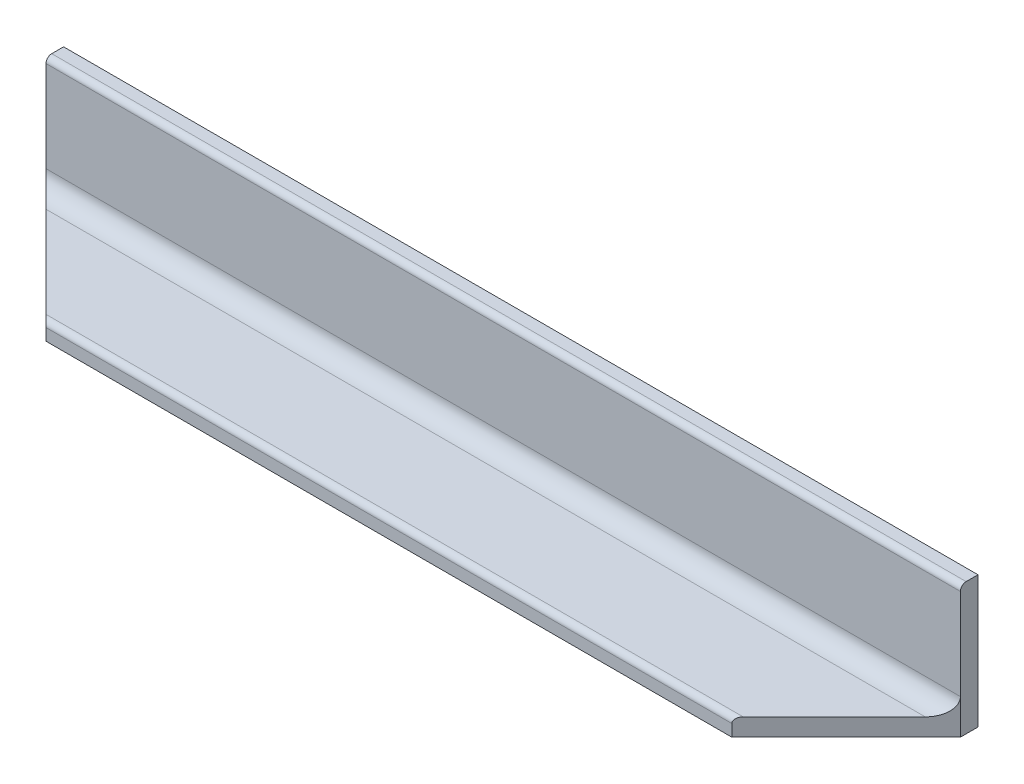
SolidWorks part; units mm, degrees
material "СТ3КП"
ref_plane "Спереди" through (0, 0, 0) normal (0, 0, 1) x (1, 0, 0)
ref_plane "Сверху" through (0, 0, 0) normal (0, 1, 0) x (1, 0, 0)
ref_plane "Справа" through (0, 0, 0) normal (1, 0, 0) x (0, 0, -1)
sketch "Эскиз1" plane through (0, 0, 0) normal (1, 0, 0) x (0, 0, -1)
  line L0 (0, -39.9784) -> (0, 49.0833) construction
  line B0 (0, 0) -> (0, 30)
  line B1 (0, 30) -> (-2.7, 30)
  line B2 (-4, 28.7) -> (-4, 8)
  line B3 (-8, 4) -> (-28.7, 4)
  line B4 (-30, 2.7) -> (-30, 0)
  line B5 (-30, 0) -> (0, 0)
  arc B6 (-2.7, 30) -> (-4, 28.7) centre (-2.7, 28.7) ccw
  arc B7 (-28.7, 4) -> (-30, 2.7) centre (-28.7, 2.7) ccw
  arc B8 (-4, 8) -> (-8, 4) centre (-8, 8) cw
sketch_block_instance "Уголок 30х30х4-1"
sketch_block "Уголок 30х30х4" parameters "D4"=1.3, "D6"=4, "D1"=30, "D2"=30, "D3"=45, "D5"=4
extrude "Бобышка-Вытянуть1" add sketch "Эскиз1" along normal mid plane 208
sketch "Эскиз2" plane through (0, 0, 0) normal (0, -1, 0) x (1, 0, 0)
  line L0 (-104, 4) -> (-78, 30)
  line L1 (104, 30) -> (-104, 30) construction
  line L2 (-78, 30) -> (-104, 30)
  line L3 (-104, 30) -> (-104, 4)
  line L4 (104, 4) -> (78, 30)
  line L5 (78, 30) -> (104, 30)
  line L6 (104, 30) -> (104, 4)
  line L7 (104, 4) -> (-104, 4) construction
extrude "Вырез-Вытянуть1" cut sketch "Эскиз2" against normal through all
move or copy body "Тело-Переместить/Копировать1" [suppressed] bodies to move or copy 103
